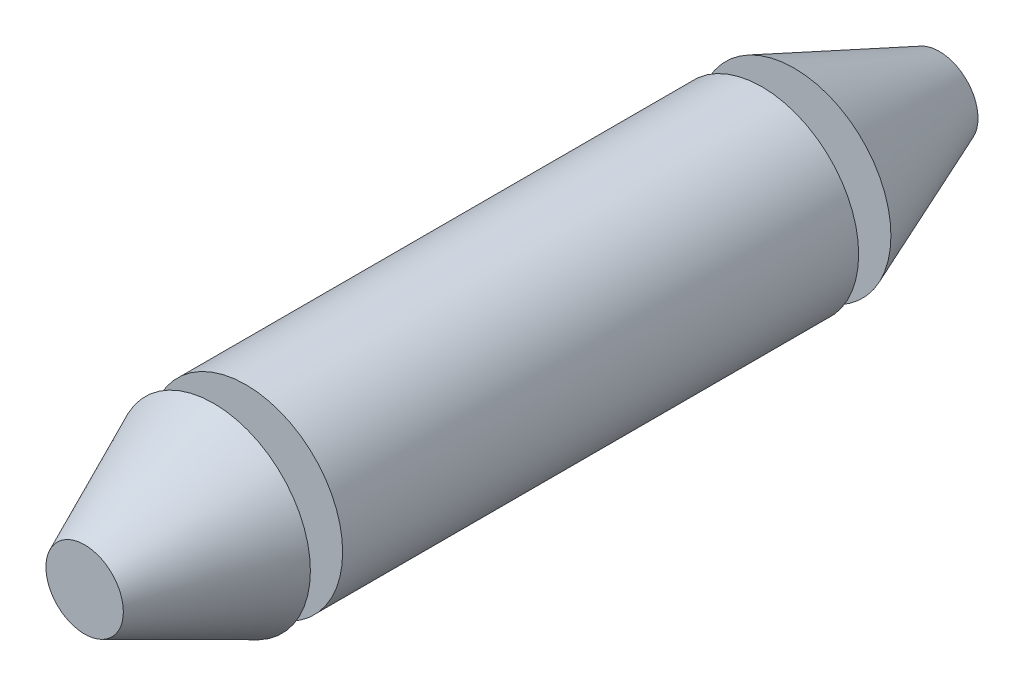
SolidWorks part; units mm, degrees
ref_plane "Face" through (0, 0, 0) normal (0, 0, 1) x (1, 0, 0)
ref_plane "Dessus" through (0, 0, 0) normal (0, 1, 0) x (1, 0, 0)
ref_plane "Droite" through (0, 0, 0) normal (1, 0, 0) x (0, 0, -1)
sketch "Esquisse1" plane through (0, 0, 0) normal (0, 0, 1) x (1, 0, 0)
  circle A0 centre (0, 0) radius 3
extrude "Extrusion1" add sketch "Esquisse1" along normal blind 16
sketch "Esquisse2" plane through (0, 0, 16) normal (0, 0, 1) x (1, 0, 0)
  circle A0 centre (0, 0) radius 1.2
extrude "Extrusion2" add sketch "Esquisse2" along normal blind 5
sketch "Esquisse3" plane through (0, 0, 0) normal (0, 0, -1) x (-1, 0, 0)
  circle A0 centre (0, 0) radius 1.2
extrude "Extrusion3" add sketch "Esquisse3" along normal blind 5.5
sketch "Esquisse4" plane through (0, 0, 0) normal (0, 1, 0) x (1, 0, 0)
  line L0 (1.2, 5.5) -> (3, 1)
  line L1 (3, 0) -> (-3, 0) construction
  line L2 (1.2, 5.5) -> (0, 5.5)
  line L3 (1.2, 5.5) -> (-1.2, 5.5) construction
  line L4 (0, 5.5) -> (0, 1)
  line L5 (0, 1) -> (3, 1)
  line L6 (0, -21) -> (1.2, -21)
  line L7 (-1.2, -21) -> (1.2, -21) construction
  line L8 (1.2, -21) -> (3, -17)
  line L9 (3, -17) -> (0, -17)
  line L10 (0, -17) -> (0, -21)
  dimension "D1" = 1
  dimension "D2" = 1
revolve "Révolution1" add sketch "Esquisse4" angle 360 about axis through (0, 0, 16) along (0, 0, -1)
